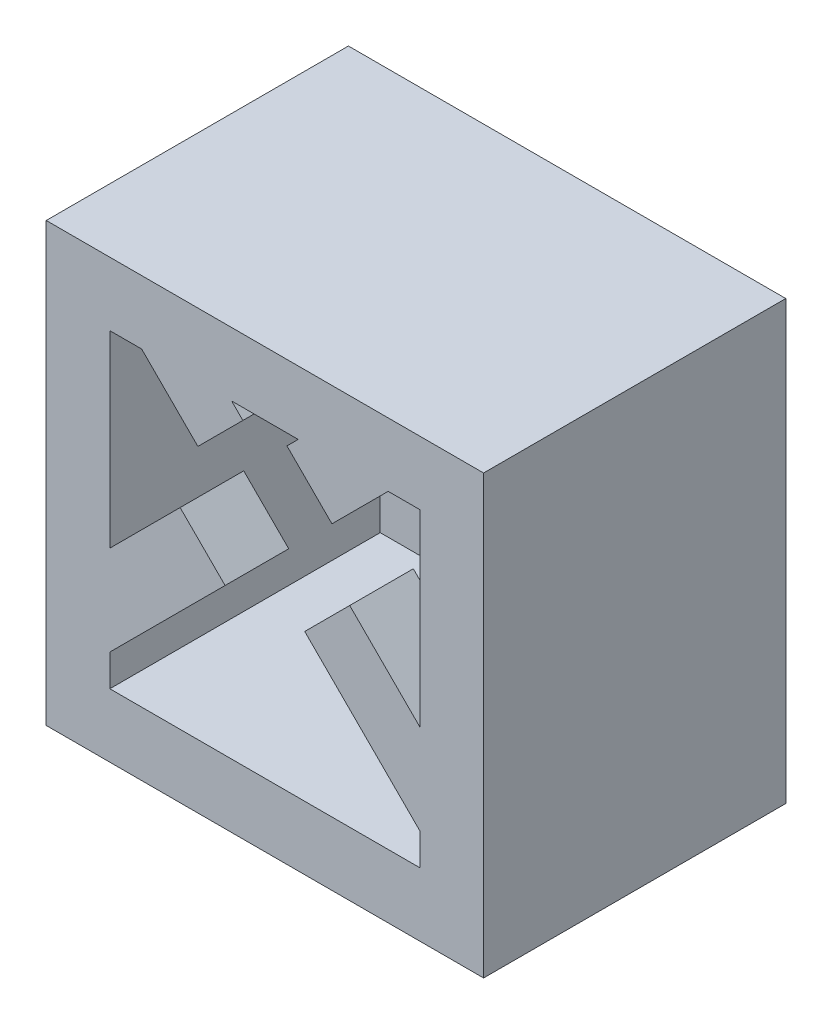
SolidWorks part; units mm, degrees
ref_plane "Front Plane" through (0, 0, 0) normal (0, 0, 1) x (1, 0, 0)
ref_plane "Top Plane" through (0, 0, 0) normal (0, 1, 0) x (1, 0, 0)
ref_plane "Right Plane" through (0, 0, 0) normal (1, 0, 0) x (0, 0, -1)
sketch "Sketch1" plane through (0, 0, 0) normal (0, 0, 1) x (1, 0, 0)
  line L1 (0, 0) -> (13.75, 0)
  line L2 (0, 0) -> (0, 13.75)
  line L3 (0, 13.75) -> (13.75, 13.75)
  line L4 (13.75, 0) -> (13.75, 13.75)
  dimension "D1" = 13.75
extrude "BaseBoss-Extrude1" add sketch "Sketch1" along normal blind 1
sketch "WallsSketch2" plane through (0, 0, 1) normal (0, 0, 1) x (1, 0, 0)
  line L0 (13.75, 13.75) -> (0, 13.75) construction
  line L1 (0, 13.75) -> (13.75, 13.75)
  line L2 (0, 13.75) -> (0, 0)
  line L3 (0, 0) -> (13.75, 0)
  line L4 (13.75, 13.75) -> (13.75, 0)
  line L5 (0, 13.75) -> (0, 0) construction
  line L7 (2, 11.75) -> (11.75, 11.75)
  line L8 (2, 11.75) -> (2, 2)
  line L9 (2, 2) -> (11.75, 2)
  line L10 (11.75, 11.75) -> (11.75, 2)
  dimension "D1" = 2
  dimension "D2" = 2
  dimension "D3" = 2
  dimension "D4" = 2
extrude "Boss-Extrude2" add sketch "WallsSketch2" along normal blind 6.5
sketch "Sketch3" plane through (0, 0, 7.5) normal (0, 0, 1) x (1, 0, 0)
  line L0 (2, 3) -> (5.6235, 6.6235)
  line L1 (2, 11.75) -> (2, 2) construction
  line L2 (11.75, 11.75) -> (2, 11.75) construction
  line L3 (7.9216, 11.75) -> (7.568, 11.3964)
  line L4 (0, 0) -> (13.75, 0) construction
  line L5 (13.75, 0) -> (13.75, 13.75) construction
  line L6 (11.75, 3) -> (8.1265, 6.6235)
  line L7 (11.75, 2) -> (11.75, 11.75) construction
  line L8 (5.8284, 11.75) -> (6.182, 11.3964)
  line L9 (4.2093, 8.0377) -> (5.6235, 6.6235)
  line L10 (9.5407, 8.0377) -> (8.1265, 6.6235)
  line L11 (6.182, 11.3964) -> (4.7678, 9.9822)
  line L12 (7.568, 11.3964) -> (8.9822, 9.9822)
  line L13 (11.75, 5.8284) -> (9.5407, 8.0377)
  line L14 (8.9822, 9.9822) -> (10.75, 11.75)
  line L15 (4.2093, 8.0377) -> (2, 5.8284)
  line L16 (4.7678, 9.9822) -> (3, 11.75)
  line L17 (2, 3) -> (2, 2)
  line L18 (2, 2) -> (11.75, 2) construction
  line L19 (2, 2) -> (11.75, 2)
  line L20 (11.75, 2) -> (11.75, 3)
  line L21 (11.75, 5.8284) -> (11.75, 11.75)
  line L22 (11.75, 11.75) -> (10.75, 11.75)
  line L23 (5.8284, 11.75) -> (7.9216, 11.75)
  line L24 (3, 11.75) -> (2, 11.75)
  line L25 (2, 11.75) -> (2, 5.8284)
  line L27 (0, 13.75) -> (13.75, 13.75)
  line L28 (0, 13.75) -> (0, 0)
  line L29 (0, 0) -> (13.75, 0)
  line L30 (13.75, 13.75) -> (13.75, 0)
  point P20 (8.2751, 10.6893)
  point P40 (10.3095, 7.2689)
  point P41 (4.9164, 7.3306)
  dimension "D1" = 3
  dimension "D2" = 3
  dimension "D4" = 2
  dimension "D3" = 2
  dimension "D5" = 4.75
  dimension "D6" = 2.5
extrude "Boss-Extrude3" add sketch "Sketch3" along normal blind 2
equation "\"D1@Sketch1\" = \"ClampWidth\""
equation "\"RibbonCableWidth\"= 6.75mm"
equation "\"RibbonCableInnerHypotonus\"= sqr ( \"RibbonCableWidth\" ^ 2 * 2 )"
equation "\"M2.5HoleDiameter\"= 2.5mm"
equation "\"FastenerTabHoleCenterFromSide\"= 2mm"
equation "\"ClampBridgeWidth\"= 2mm"
equation "\"ClampWidth\"= \"RibbonCableWidth\" + \"ClampBridgeWidth\" * 2 + \"RibbonCableClampStretchWidth\""
equation "\"ClampBridgeHeight\"= 6.5mm"
equation "\"BaseBoss\"= 1mm"
equation "\"RibbonCableLowerWallHeight\"= 2mm"
equation "\"RibbonCableOuterHypotonus\"= sqr ( ( \"ClampBridgeWidth\" ^ 2 ) * 2 ) + \"RibbonCableInnerHypotonus\" + sqr ( ( \"ClampBridgeWidth\" ^ 2 ) * 2 )"
equation "\"RibbonCableHeight\"=2"
equation "\"RibbonCableClampStretchWidth\"= 3mm"
equation "\"D1@BaseBoss-Extrude1\" = \"BaseBoss\""
equation "\"D1@WallsSketch2\" = \"ClampBridgeWidth\""
equation "\"D2@WallsSketch2\" = \"ClampBridgeWidth\""
equation "\"D3@WallsSketch2\" = \"ClampBridgeWidth\""
equation "\"D4@WallsSketch2\" = \"ClampBridgeWidth\""
equation "\"D1@Boss-Extrude2\"=\"ClampBridgeHeight\""
equation "\"D1@Sketch3\"=\"RibbonCableClampStretchWidth\""
equation "\"D2@Sketch3\"=\"RibbonCableClampStretchWidth\""
equation "\"D4@Sketch3\"=\"ClampBridgeWidth\""
equation "\"D3@Sketch3\"=\"ClampBridgeWidth\""
